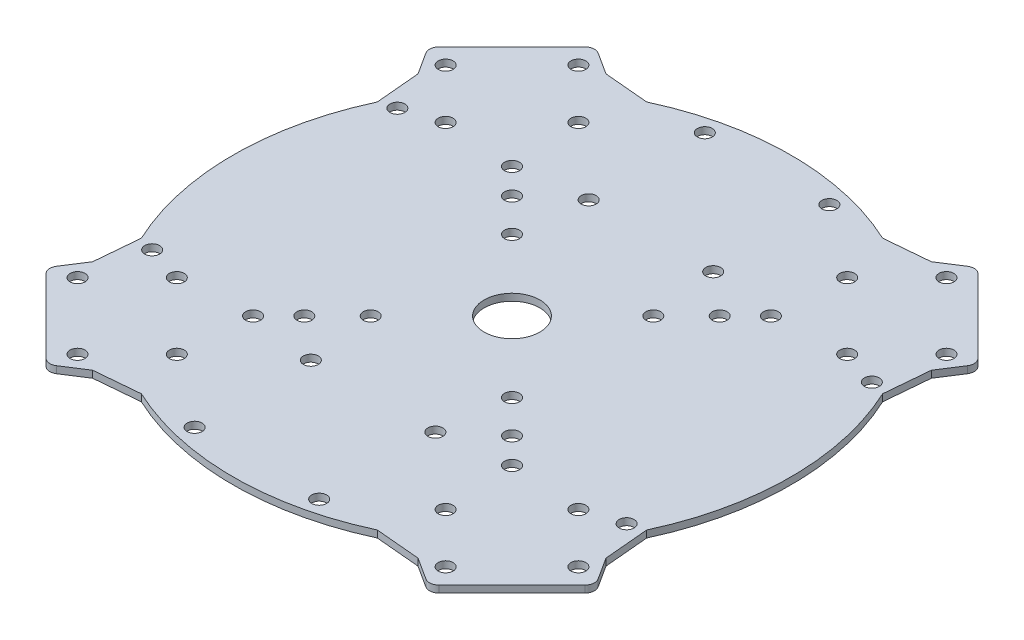
SolidWorks part; units mm, degrees
ref_plane "前视基准面" through (0, 0, 0) normal (0, 0, 1) x (1, 0, 0)
ref_plane "上视基准面" through (0, 0, 0) normal (0, 1, 0) x (1, 0, 0)
ref_plane "右视基准面" through (0, 0, 0) normal (1, 0, 0) x (0, 0, -1)
other "Configuration Table"
sketch "草图1" plane through (0, 0, 0) normal (0, 1, 0) x (1, 0, 0)
  line L5 (0, 0) -> (120.9074, 0) construction
  line L6 (-70.9, -70.9) -> (70.9, 70.9) construction
  line L7 (41.1183, 59.1495) -> (59.1495, 41.1183)
  line L8 (58.0107, -42.257) -> (42.257, -58.0107)
  line L9 (-42.257, -58.0107) -> (-58.0107, -42.257)
  line L10 (-58.0107, 42.257) -> (-42.257, 58.0107)
  line L11 (42.257, 58.0107) -> (58.0107, 42.257)
  line L13 (58.2798, 39.7628) -> (55.225, 35.0018)
  line L14 (39.7628, 58.2798) -> (35.0018, 55.225)
  line L15 (55.225, 35.0018) -> (54.3689, 25.3775)
  line L16 (35.0018, 55.225) -> (25.3775, 54.3689)
  line L18 (55.225, -35.0018) -> (54.3689, -25.3775)
  line L20 (35.0018, -55.225) -> (25.3775, -54.3689)
  line L21 (39.7628, -58.2798) -> (35.0018, -55.225)
  line L22 (58.2798, -39.7628) -> (55.225, -35.0018)
  line L24 (-35.0018, -55.225) -> (-25.3775, -54.3689)
  line L26 (-55.225, -35.0018) -> (-54.3689, -25.3775)
  line L27 (-58.2798, -39.7628) -> (-55.225, -35.0018)
  line L28 (-39.7628, -58.2798) -> (-35.0018, -55.225)
  line L30 (-55.225, 35.0018) -> (-54.3689, 25.3775)
  line L32 (-35.0018, 55.225) -> (-25.3775, 54.3689)
  line L33 (-39.7628, 58.2798) -> (-35.0018, 55.225)
  line L34 (-58.2798, 39.7628) -> (-55.225, 35.0018)
  line L35 (39.598, 53.8815) -> (28.9207, 43.2042) construction
  line L36 (0, 0) -> (0, 60) construction
  arc A0 (25.3775, 54.3689) -> (-25.3775, 54.3689) centre (0, 0) ccw
  arc A1 (54.3689, -25.3775) -> (54.3689, 25.3775) centre (0, 0) ccw
  arc A2 (-54.3689, 25.3775) -> (-54.3689, -25.3775) centre (0, 0) ccw
  arc A3 (-25.3775, -54.3689) -> (25.3775, -54.3689) centre (0, 0) ccw
  circle A4 centre (39.598, 53.8815) radius 1.6
  circle A5 centre (53.8815, 39.598) radius 1.6
  circle A6 centre (28.9207, 43.2042) radius 1.6
  circle A7 centre (43.2042, 28.9207) radius 1.6
  circle A8 centre (27.86, 27.86) radius 1.6
  circle A9 centre (22.3446, 22.3446) radius 1.6
  circle A10 centre (15.2028, 15.2028) radius 1.6
  circle A11 centre (13.4, 54.888) radius 1.6
  circle A12 centre (13.4, 29.888) radius 1.6
  circle A13 centre (-13.4, 29.888) radius 1.6
  circle A14 centre (-13.4, 54.888) radius 1.6
  circle A15 centre (51.045, 26.3832) radius 1.6
  circle A16 centre (-15.2028, 15.2028) radius 1.6
  circle A17 centre (-22.3446, 22.3446) radius 1.6
  circle A18 centre (-27.86, 27.86) radius 1.6
  circle A19 centre (-43.2042, 28.9207) radius 1.6
  circle A20 centre (-51.045, 26.3832) radius 1.6
  circle A21 centre (-28.9207, 43.2042) radius 1.6
  circle A22 centre (-53.8815, 39.598) radius 1.6
  circle A23 centre (-39.598, 53.8815) radius 1.6
  circle A24 centre (43.2042, -28.9207) radius 1.6
  circle A25 centre (51.045, -26.3832) radius 1.6
  circle A26 centre (53.8815, -39.598) radius 1.6
  circle A27 centre (39.598, -53.8815) radius 1.6
  circle A28 centre (28.9207, -43.2042) radius 1.6
  circle A29 centre (27.86, -27.86) radius 1.6
  circle A30 centre (22.3446, -22.3446) radius 1.6
  circle A31 centre (15.2028, -15.2028) radius 1.6
  circle A32 centre (13.4, -29.888) radius 1.6
  circle A33 centre (13.4, -54.888) radius 1.6
  circle A34 centre (-13.4, -29.888) radius 1.6
  circle A35 centre (-15.2028, -15.2028) radius 1.6
  circle A36 centre (-22.3446, -22.3446) radius 1.6
  circle A37 centre (-27.86, -27.86) radius 1.6
  circle A38 centre (-13.4, -54.888) radius 1.6
  circle A39 centre (-28.9207, -43.2042) radius 1.6
  circle A40 centre (-43.2042, -28.9207) radius 1.6
  circle A41 centre (-51.045, -26.3832) radius 1.6
  circle A42 centre (-39.598, -53.8815) radius 1.6
  circle A43 centre (-53.8815, -39.598) radius 1.6
  circle A44 centre (0, 0) radius 6
  arc A45 (42.257, 58.0107) -> (39.7628, 58.2798) centre (40.8428, 56.5965) ccw
  arc A46 (58.0107, 42.257) -> (58.2798, 39.7628) centre (56.5965, 40.8428) cw
  arc A47 (58.2798, -39.7628) -> (58.0107, -42.257) centre (56.5965, -40.8428) cw
  arc A48 (39.7628, -58.2798) -> (42.257, -58.0107) centre (40.8428, -56.5965) ccw
  arc A49 (-39.7628, -58.2798) -> (-42.257, -58.0107) centre (-40.8428, -56.5965) cw
  arc A50 (-58.2798, -39.7628) -> (-58.0107, -42.257) centre (-56.5965, -40.8428) ccw
  arc A51 (-58.2798, 39.7628) -> (-58.0107, 42.257) centre (-56.5965, 40.8428) cw
  arc A52 (-39.7628, 58.2798) -> (-42.257, 58.0107) centre (-40.8428, 56.5965) ccw
  point P20 (0, 0)
  point P39 (0, 0)
  dimension "D1" = 120
  dimension "D10" = 3.2
  dimension "D11" = 4.8
  dimension "D13" = 3.2
  dimension "D15" = 3.2
  dimension "D18" = 3.2
  dimension "D19" = 3.2
  dimension "D21" = 3.2
  dimension "D22" = 3.2
  dimension "D24" = 56.5
  dimension "D26" = 3.2
  dimension "D29" = 70.9
  dimension "D8" = 12
  dimension "D30" = 2
  dimension "D2" = 45
  dimension "D3" = 41
  dimension "D4" = 5.083
  dimension "D5" = 4
  dimension "D6" = 25.5
  dimension "D7" = 28.6
  dimension "D9" = 4
  dimension "D12" = 20.2
  dimension "D14" = 15.1
  dimension "D16" = 31.5
  dimension "D17" = 39.3
  dimension "D20" = 49.4
  dimension "D23" = 25
  dimension "D25" = 26.8
  dimension "D27" = 3.4
  dimension "D28" = 16.15
  dimension "D31" = 70.9
  dimension "D32" = 70.9
extrude "凸台-拉伸2" add sketch "草图1" along normal blind 1.5 contours L33 A52 L10 A51 L34 L30 A2 L26 L27 A50 L9 A49 L28 L24 A3 L20 L21 A48 L8 A47 L22 L18 A1 L15 L13 A46 L7 A45 L14 L16 A0 L32 A43 A42 A41 A33 A31 A29 A27 A26 A23
